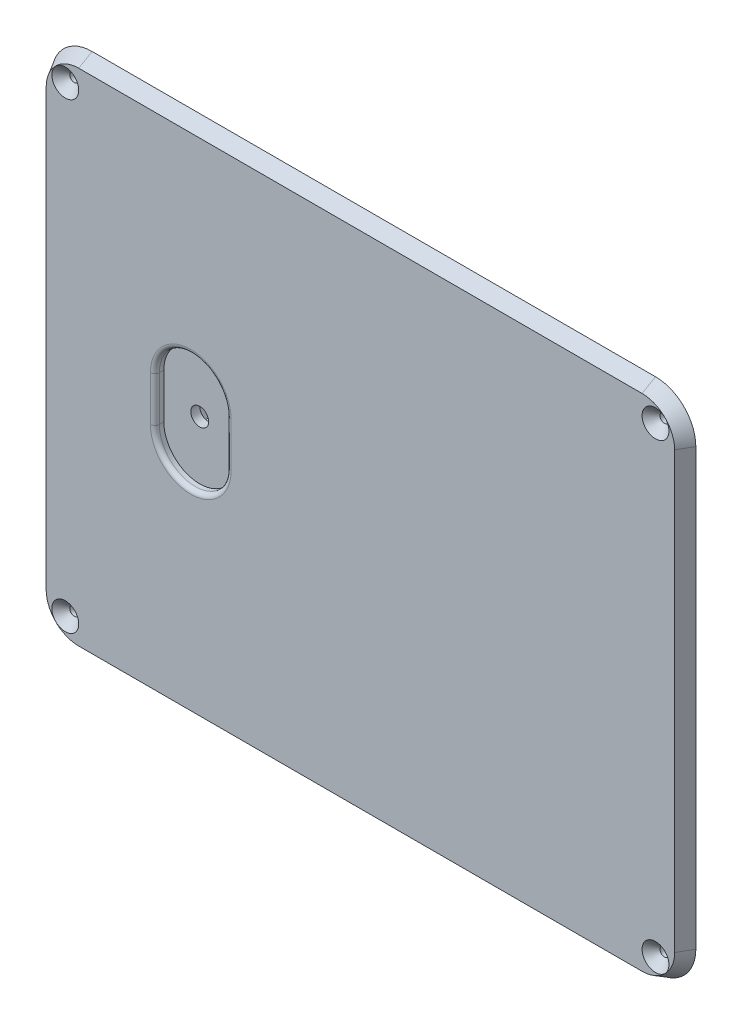
SolidWorks part; units mm, degrees
ref_plane "Спереди" through (0, 0, 0) normal (0, 0, 1) x (1, 0, 0)
ref_plane "Сверху" through (0, 0, 0) normal (0, 1, 0) x (1, 0, 0)
ref_plane "Справа" through (0, 0, 0) normal (1, 0, 0) x (0, 0, -1)
other "Графика1"
sketch "Эскиз2" plane through (0, 0, 0) normal (0, 0, 1) x (1, 0, 0)
  line L37 (4305.3301, -2844.2449) -> (4305.3301, -2941.3999)
  line L38 (4296.3301, -2950.3999) -> (4170.6001, -2950.3999)
  line L39 (4161.6001, -2844.2449) -> (4161.6001, -2941.3999)
  line L40 (4296.3301, -2835.2449) -> (4170.6001, -2835.2449)
  line L41 (4233.4651, -2838.2449) -> (4233.4651, -2947.3999) construction
  line L42 (4164.6001, -2892.8224) -> (4302.3301, -2892.8224) construction
  arc A8 (4305.3301, -2941.3999) -> (4296.3301, -2950.3999) centre (4296.3301, -2941.3999) cw
  arc A9 (4170.6001, -2950.3999) -> (4161.6001, -2941.3999) centre (4170.6001, -2941.3999) cw
  arc A10 (4161.6001, -2844.2449) -> (4170.6001, -2835.2449) centre (4170.6001, -2844.2449) cw
  arc A11 (4305.3301, -2844.2449) -> (4296.3301, -2835.2449) centre (4296.3301, -2844.2449) ccw
  dimension "D2" = 109.155
  dimension "D6" = 125.73
extrude "Бобышка-Вытянуть1" add sketch "Эскиз2" along normal blind 3 draft 30
sketch "Эскиз10" plane through (0, 0, 3) normal (0, 0, 1) x (1, 0, 0)
  line L7 (4233.4651, -2838.2449) -> (4233.4651, -2950.3999) construction
  line L8 (4296.3301, -2950.3999) -> (4170.6001, -2950.3999) construction
  line L9 (4164.6001, -2892.8224) -> (4302.3301, -2892.8224) construction
  circle A2 centre (4167.6001, -2841.2449) radius 1
  circle A3 centre (4299.3301, -2841.2449) radius 1
  circle A6 centre (4167.6001, -2944.3999) radius 1
  circle A11 centre (4299.3301, -2944.3999) radius 1
extrude "Вырез-Вытянуть1" cut sketch "Эскиз10" against normal blind 10
chamfer "Фаска1" distance 2 angle 45 4 edges at (4166.6001, -2944.3999, 3) (4300.3301, -2944.3999, 3) (4298.3301, -2841.2449, 3) (4168.6001, -2841.2449, 3)
sketch "Эскиз11" plane through (0, 0, 0) normal (0, 0, -1) x (-1, 0, 0)
  line L4 (-4301.3301, -2846.2449) -> (-4301.3301, -2939.3999)
  line L5 (-4294.3301, -2946.3999) -> (-4172.6001, -2946.3999)
  line L6 (-4165.6001, -2939.3999) -> (-4165.6001, -2846.2449)
  line L7 (-4172.6001, -2839.2449) -> (-4294.3301, -2839.2449)
  line L10 (-4305.3301, -2892.8224) -> (-4161.6001, -2892.8224) construction
  line L11 (-4305.3301, -2844.2449) -> (-4305.3301, -2941.3999) construction
  line L12 (-4161.6001, -2844.2449) -> (-4161.6001, -2941.3999) construction
  line L19 (-4233.4651, -2835.2449) -> (-4233.4651, -2950.3999) construction
  line L20 (-4296.3301, -2835.2449) -> (-4170.6001, -2835.2449) construction
  line L21 (-4296.3301, -2950.3999) -> (-4170.6001, -2950.3999) construction
  line L22 (-4294.3301, -2841.2449) -> (-4294.3301, -2839.2449)
  line L23 (-4299.3301, -2846.2449) -> (-4301.3301, -2846.2449)
  line L24 (-4167.6001, -2846.2449) -> (-4165.6001, -2846.2449)
  line L25 (-4172.6001, -2841.2449) -> (-4172.6001, -2839.2449)
  line L26 (-4167.6001, -2939.3999) -> (-4165.6001, -2939.3999)
  line L27 (-4172.6001, -2944.3999) -> (-4172.6001, -2946.3999)
  line L28 (-4294.3301, -2944.3999) -> (-4294.3301, -2946.3999)
  line L29 (-4299.3301, -2939.3999) -> (-4301.3301, -2939.3999)
  arc A24 (-4299.3301, -2846.2449) -> (-4294.3301, -2841.2449) centre (-4299.3301, -2841.2449) ccw
  arc A25 (-4167.6001, -2846.2449) -> (-4172.6001, -2841.2449) centre (-4167.6001, -2841.2449) cw
  arc A26 (-4167.6001, -2939.3999) -> (-4172.6001, -2944.3999) centre (-4167.6001, -2944.3999) ccw
  arc A27 (-4299.3301, -2939.3999) -> (-4294.3301, -2944.3999) centre (-4299.3301, -2944.3999) cw
  dimension "D1" = 131.73
extrude "Бобышка-Вытянуть2" add sketch "Эскиз11" along normal blind 1 draft 6
sketch "Эскиз17" plane through (0, 0, -1) normal (0, 0, -1) x (-1, 0, 0)
  line L0 (-4172.6001, -2871.0799) -> (-4172.6001, -2876.1999) construction
  line L1 (-4172.6001, -2876.1999) -> (-4172.6001, -2881.3199) construction
  line L2 (-4172.6001, -2881.3199) -> (-4172.6001, -2886.4399) construction
  line L3 (-4172.6001, -2886.4399) -> (-4172.6001, -2891.5599) construction
  line L4 (-4172.6001, -2891.5599) -> (-4172.6001, -2896.6799) construction
  line L5 (-4172.6001, -2896.6799) -> (-4172.6001, -2901.7999) construction
  line L6 (-4172.6001, -2901.7999) -> (-4172.6001, -2906.9199) construction
  line L7 (-4172.6001, -2906.9199) -> (-4172.6001, -2912.0399) construction
  line L8 (-4172.6001, -2912.0399) -> (-4172.6001, -2917.1599) construction
  line L9 (-4172.6001, -2917.1599) -> (-4172.6001, -2922.2799) construction
  line L10 (-4172.6001, -2922.2799) -> (-4172.6001, -2927.3999) construction
  line L12 (-4161.6001, -2844.2449) -> (-4161.6001, -2941.3999) construction
  line L13 (-4305.3301, -2844.2449) -> (-4305.3301, -2941.3999) construction
  line L14 (-4296.3301, -2950.3999) -> (-4170.6001, -2950.3999) construction
  circle A0 centre (-4172.6001, -2871.0799) radius 2.5
  circle A1 centre (-4172.6001, -2876.1999) radius 2.5
  circle A2 centre (-4172.6001, -2881.3199) radius 2.5
  circle A3 centre (-4172.6001, -2886.4399) radius 2.5
  circle A4 centre (-4172.6001, -2891.5599) radius 2.5
  circle A5 centre (-4172.6001, -2896.6799) radius 2.5
  circle A6 centre (-4172.6001, -2901.7999) radius 2.5
  circle A7 centre (-4172.6001, -2906.9199) radius 2.5
  circle A8 centre (-4172.6001, -2912.0399) radius 2.5
  circle A9 centre (-4172.6001, -2917.1599) radius 2.5
  circle A10 centre (-4172.6001, -2922.2799) radius 2.5
  circle A11 centre (-4172.6001, -2927.3999) radius 2.5
  dimension "D1" = 23
  dimension "D2" = 11
  dimension "D3" = 143.73
extrude "Вырез-Вытянуть4" cut sketch "Эскиз17" against normal blind 2.4
sketch "Эскиз12" plane through (0, 0, 3) normal (0, 0, 1) x (1, 0, 0)
  line L7 (4193.6001, -2892.8224) -> (4197.6001, -2892.8224) construction
  line L9 (4187.6001, -2897.8224) -> (4187.6001, -2887.8224)
  line L11 (4203.6001, -2897.8224) -> (4203.6001, -2887.8224)
  line L13 (4161.6001, -2844.2449) -> (4161.6001, -2941.3999) construction
  line L14 (4194.5519, -2894.5257) -> (4196.6483, -2891.1191) construction
  line L19 (4195.6001, -2890.8224) -> (4195.6001, -2894.8224) construction
  line L20 (4194.5519, -2891.1191) -> (4196.6483, -2894.5257) construction
  circle A0 centre (4195.6001, -2892.8224) radius 2 construction
  arc A2 (4187.6001, -2897.8224) -> (4203.6001, -2897.8224) centre (4195.6001, -2897.8224) ccw
  arc A3 (4203.6001, -2887.8224) -> (4187.6001, -2887.8224) centre (4195.6001, -2887.8224) ccw
  dimension "D2" = 34
extrude "Вырез-Вытянуть2" cut sketch "Эскиз12" against normal blind 2
fillet "Скругление1" radius 1 4 edges at (4195.6001, -2905.8224, 3) (4187.6001, -2892.8224, 3) (4195.6001, -2879.8224, 3) (4203.6001, -2892.8224, 3)
sketch "Эскиз13" plane through (0, 0, 1) normal (0, 0, 1) x (1, 0, 0)
  circle A0 centre (4195.6001, -2892.8224) radius 2
extrude "Вырез-Вытянуть3" cut sketch "Эскиз13" against normal through all
sketch "Эскиз14" plane through (0, 0, -1) normal (0, 0, -1) x (-1, 0, 0)
  line L1 (-4193.7269, -2889.2413) -> (-4197.7649, -2889.4096)
  line L2 (-4197.7649, -2889.4096) -> (-4199.638, -2892.9908)
  line L3 (-4199.638, -2892.9908) -> (-4197.4732, -2896.4036)
  line L4 (-4197.4732, -2896.4036) -> (-4193.4353, -2896.2352)
  line L5 (-4193.4353, -2896.2352) -> (-4191.5622, -2892.654)
  line L6 (-4191.5622, -2892.654) -> (-4193.7269, -2889.2413)
  circle A0 centre (-4195.6001, -2892.8224) radius 3.5 construction
  circle A1 centre (-4195.6001, -2892.8224) radius 14.5
  point P1 (-4195.7459, -2889.3254)
  dimension "D2" = 29
  dimension "D1" = 7
extrude "Бобышка-Вытянуть3" add sketch "Эскиз14" along normal blind 3.2
fillet "Скругление2" radius 2 1 edges at (4181.1001, -2892.8224, -4.2)
